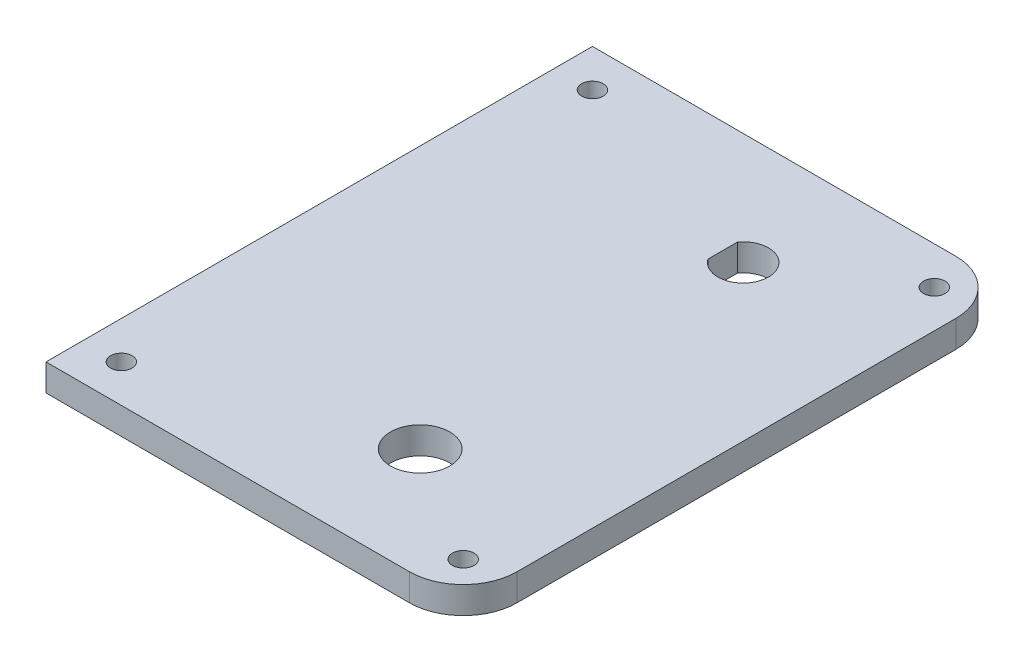
SolidWorks part; units mm, degrees
ref_plane "Front Plane" through (0, 0, 0) normal (0, 0, 1) x (1, 0, 0)
ref_plane "Top Plane" through (0, 0, 0) normal (0, 1, 0) x (1, 0, 0)
ref_plane "Right Plane" through (0, 0, 0) normal (1, 0, 0) x (0, 0, -1)
sketch "Sketch3" plane through (0, 0, 0) normal (0, 1, 0) x (1, 0, 0)
  line L0 (-38.75, 50.75) -> (28.75, 50.75)
  line L1 (-38.75, 50.75) -> (-38.75, -50.75)
  line L2 (-38.75, -50.75) -> (28.75, -50.75)
  line L3 (38.75, 40.75) -> (38.75, -40.75)
  line L5 (6.1885, 32.75) -> (6.1885, 27.25)
  line L27 (-55, 0) -> (55, 0) construction
  line L28 (0, -55) -> (0, 55) construction
  arc A0 (28.75, 50.75) -> (38.75, 40.75) centre (28.75, 40.75) cw
  arc A1 (38.75, -40.75) -> (28.75, -50.75) centre (28.75, -40.75) cw
  circle A8 centre (-31.75, -43.75) radius 2
  circle A9 centre (-31.75, 43.75) radius 2
  circle A10 centre (31.75, 43.75) radius 2
  circle A11 centre (31.75, -43.75) radius 2
  arc A14 (6.1885, 27.25) -> (6.1885, 32.75) centre (10, 30) ccw
  circle A15 centre (10, -30) radius 5.5
  dimension "D1" = 4
  dimension "D4" = 4
  dimension "D6" = 4
  dimension "D7" = 4
  dimension "D8" = 7
  dimension "D9" = 7
  dimension "D10" = 7
  dimension "D11" = 7
  dimension "D12" = 7
  dimension "D13" = 7
  dimension "D14" = 9.4
  dimension "D15" = 5.5
  dimension "D16" = 10
  dimension "D17" = 30
  dimension "D26" = 10
  dimension "D27" = 10
  dimension "D3" = 7
  dimension "D5" = 7
  dimension "D22" = 11
  dimension "D23" = 30
  dimension "D24" = 10
  dimension "D18" = 50.75
  dimension "D19" = 50.75
  dimension "D20" = 38.75
  dimension "D21" = 38.75
extrude "Boss-Extrude2" add sketch "Sketch3" along normal blind 5
